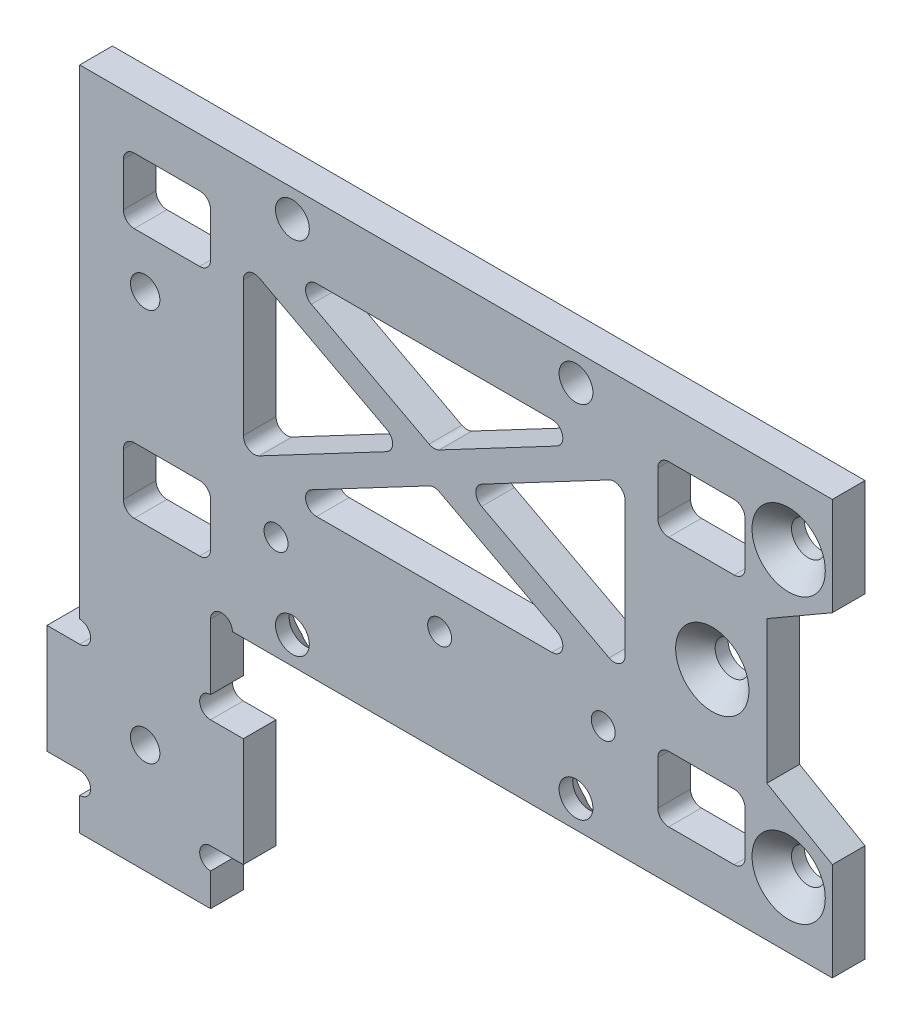
SolidWorks part; units mm, degrees
material "Thornel Mat VMA"
ref_plane "前视基准面" through (0, 0, 0) normal (0, 0, 1) x (1, 0, 0)
ref_plane "上视基准面" through (0, 0, 0) normal (0, 1, 0) x (1, 0, 0)
ref_plane "右视基准面" through (0, 0, 0) normal (1, 0, 0) x (0, 0, -1)
sketch "草图1" plane through (0, 0, 0) normal (0, 0, 1) x (1, 0, 0)
  line L0 (0, 0) -> (-12.4597, 0) construction
  line L1 (13, -16.5) -> (-13, -16.5) construction
  line L2 (13, -16.5) -> (13, 16.5) construction
  line L3 (13, 16.5) -> (-13, 16.5) construction
  line L4 (-13, -16.5) -> (-13, 16.5) construction
  line L5 (13, -16.5) -> (-13, 16.5) construction
  line L6 (13, 16.5) -> (-13, -16.5) construction
  line L7 (0, 0) -> (0, 10.3016) construction
  line L8 (-20.5, -14.5) -> (-28.5, -14.5)
  line L9 (36.5, -19) -> (-32.5, -19)
  line L10 (36.5, -19) -> (36.5, 19) construction
  line L12 (-36.5, -19) -> (-36.5, 19) construction
  line L13 (36.5, -19) -> (-36.5, 19) construction
  line L14 (36.5, 19) -> (-36.5, -19) construction
  line L15 (-20.5, 8.5) -> (-28.5, 8.5)
  line L16 (-20.5, 8.5) -> (-20.5, 14.5)
  line L17 (-20.5, 14.5) -> (-28.5, 14.5)
  line L18 (-28.5, 8.5) -> (-28.5, 14.5)
  line L19 (-20.5, 8.5) -> (-28.5, 14.5) construction
  line L20 (-20.5, 14.5) -> (-28.5, 8.5) construction
  line L21 (-28.5, -8.5) -> (-28.5, -14.5)
  line L22 (-20.5, -8.5) -> (-28.5, -8.5)
  line L23 (-20.5, -8.5) -> (-20.5, -14.5)
  line L24 (20.5, -8.5) -> (20.5, -14.5)
  line L25 (20.5, -8.5) -> (28.5, -8.5)
  line L26 (28.5, -8.5) -> (28.5, -14.5)
  line L27 (20.5, -14.5) -> (28.5, -14.5)
  line L28 (20.5, 14.5) -> (28.5, 14.5)
  line L29 (28.5, 8.5) -> (28.5, 14.5)
  line L30 (20.5, 8.5) -> (28.5, 8.5)
  line L31 (20.5, 8.5) -> (20.5, 14.5)
  line L32 (-28.5, -11.5) -> (-24.5, -11.5) construction
  line L33 (24.5, 14.5) -> (24.5, 12.5) construction
  line L34 (36.5, 19) -> (36.5, 10)
  line L35 (-32.5, 19) -> (-32.5, -19)
  line L44 (36.5, 19) -> (-32.5, 19)
  line L71 (32.5, 13) -> (32.5, -13) construction
  line L72 (25.5, 0) -> (32.5, 0) construction
  line L75 (36.5, 10) -> (30.5, 6.5359)
  line L76 (30.5, 6.5359) -> (30.5, -6.5359)
  line L77 (30.5, -6.5359) -> (36.5, -10)
  line L79 (36.5, -10) -> (36.5, -19)
  circle A0 centre (-13, 16.5) radius 1.55
  circle A1 centre (-13, -16.5) radius 1.55
  circle A2 centre (13, -16.5) radius 1.55
  circle A3 centre (13, 16.5) radius 1.55
  circle A4 centre (-32.5, 13) radius 1.55 construction
  circle A5 centre (-32.5, -13) radius 1.55 construction
  circle A6 centre (32.5, -13) radius 1.55
  circle A7 centre (32.5, 13) radius 1.55
  circle A18 centre (25.5, 0) radius 1.55
  point P0 (0, 0)
  point P25 (-24.5, 11.5)
  dimension "D1" = 3.1
  dimension "D2" = 33
  dimension "D3" = 26
  dimension "D4" = 26
  dimension "D5" = 65
  dimension "D6" = 2.5
  dimension "D7" = 4
  dimension "D8" = 6
  dimension "D9" = 8
  dimension "D10" = 49
  dimension "D11" = 23
  dimension "D15" = 4
  dimension "D23" = 7
  dimension "D24" = 9
  dimension "D25" = 5
  dimension "D26" = 60
extrude "凸台-拉伸1" add sketch "草图1" along normal blind 3
hole_wizard "M3 六角凹锥坑螺钉的锥形沉头孔1" positions "3D草图1" profile "草图2" countersink size "M3" standard "ISO" end condition through all
sketch3d "3D草图1"
  line L4 (32.5, 13, 3) -> (32.5, 13, 0) construction
  line L5 (25.5, 0, 3) -> (25.5, 0, 0) construction
  line L6 (32.5, -13, 3) -> (32.5, -13, 0) construction
  point P16 (32.5, 13, 3)
  point P20 (25.5, 0, 3)
  point P24 (32.5, -13, 3)
sketch "草图2" plane through (32.5, 13, 3) normal (1, 0, 0) x (0, -1, 0)
  line L0 (0, 0) -> (0, 3)
  line L1 (0, 3) -> (1.5, 3)
  line L2 (1.5, 3) -> (1.5, 1.86)
  line L3 (1.5, 1.86) -> (3.36, 0)
  line L5 (3.36, 0) -> (0, 0)
  line L6 (-1.5, 1.86) -> (-3.36, 0) construction
  line L11 (0, -6.35) -> (0, 107.95) construction
  dimension "通孔孔直径" = 3
  dimension "通孔孔深度" = 3
  dimension "近端锥形沉头孔直径" = 6.72
  dimension "近端锥形沉头孔角度" = 90
sketch "草图3" plane through (0, 0, 0) normal (0, 0, -1) x (-1, 0, 0)
  line L0 (14.5, -9.5) -> (-0.5, -9.5) construction
  line L1 (32.5, -19) -> (-36.5, -19) construction
  line L2 (26.5, 19) -> (26.5, 4) construction
  line L3 (-36.5, 19) -> (32.5, 19) construction
  line L4 (32.5, 19) -> (32.5, -19) construction
  line L5 (20.5, 8.5) -> (20.5, 14.5) construction
  line L6 (17.5, 12.5) -> (-17.5, 12.5) construction
  line L7 (17.5, 12.5) -> (17.5, -6) construction
  line L8 (17.5, -6) -> (-17.5, -6) construction
  line L9 (-17.5, 12.5) -> (-17.5, -6) construction
  line L10 (17.5, 12.5) -> (-17.5, -6) construction
  line L11 (17.5, -6) -> (-17.5, 12.5) construction
  line L12 (-20.5, 14.5) -> (-20.5, 8.5) construction
  line L13 (14.8251, -6) -> (0, 1.8361)
  line L14 (0, 1.8361) -> (-14.8251, -6)
  line L15 (-14.8251, -6) -> (14.8251, -6)
  line L16 (17.5, -4.5861) -> (2.6749, 3.25)
  line L17 (2.6749, 3.25) -> (17.5, 11.0861)
  line L18 (17.5, 11.0861) -> (17.5, -4.5861)
  line L19 (0, 12.5) -> (0, 3.25) construction
  line L20 (0, 3.25) -> (-17.5, 3.25) construction
  line L21 (0, 4.6639) -> (-14.8251, 12.5)
  line L22 (14.8251, 12.5) -> (0, 4.6639)
  line L23 (-14.8251, 12.5) -> (14.8251, 12.5)
  line L24 (-2.6749, 3.25) -> (-17.5, 11.0861)
  line L25 (-17.5, -4.5861) -> (-2.6749, 3.25)
  line L26 (-17.5, 11.0861) -> (-17.5, -4.5861)
  circle A0 centre (14.5, -9.5) radius 1.1
  circle A1 centre (-0.5, -9.5) radius 1.1
  circle A2 centre (-15.5, -9.5) radius 1.1
  circle A3 centre (26.5, 4) radius 1.35
  circle A4 centre (13, 16.5) radius 1.55 construction
  point P16 (0, 3.25)
  dimension "D3" = 2.2
  dimension "D6" = 15
  dimension "D8" = 2.7
  dimension "D2" = 9.5
  dimension "D4" = 15
  dimension "D5" = 0.5
  dimension "D7" = 6
  dimension "D9" = 3
  dimension "D10" = 3
  dimension "D11" = 4
  dimension "D12" = 3.5
  dimension "D13" = 2.5
  dimension "D1" = 3
extrude "切除-拉伸1" cut sketch "草图3" against normal through all
sketch "草图4" plane through (0, 0, 0) normal (0, 0, -1) x (-1, 0, 0)
  line L5 (32.5, -19) -> (20.5, -19)
  line L6 (32.5, -19) -> (32.5, -22)
  line L7 (32.5, -22) -> (20.5, -22) construction
  line L8 (20.5, -19) -> (20.5, -22)
  line L9 (26.5, -22) -> (26.5, -19) construction
  line L10 (32.5, -20.5) -> (20.5, -20.5) construction
  line L11 (32.5, -22) -> (20.5, -22) construction
  line L12 (32.5, -22) -> (32.5, -27)
  line L13 (32.5, -42) -> (20.5, -42)
  line L14 (20.5, -22) -> (20.5, -27)
  line L15 (26.5, -42) -> (26.5, -22) construction
  line L16 (35.5, -32) -> (17.5, -32) construction
  line L17 (35.5, -27) -> (32.5, -27)
  line L18 (35.5, -27) -> (35.5, -37)
  line L19 (35.5, -37) -> (32.5, -37)
  line L21 (35.5, -27) -> (32.5, -37) construction
  line L22 (35.5, -37) -> (32.5, -27) construction
  line L26 (20.5, -37) -> (20.5, -42)
  line L27 (32.5, -37) -> (32.5, -42)
  line L28 (32.5, -19) -> (-36.5, -19) construction
  line L29 (5.5, -22) -> (-5.5, -22) construction
  line L30 (5.5, -22) -> (5.5, -19) construction
  line L31 (5.5, -19) -> (-5.5, -19) construction
  line L32 (-5.5, -22) -> (-5.5, -19) construction
  line L33 (0, -19) -> (0, -22) construction
  line L34 (5.5, -20.5) -> (-5.5, -20.5) construction
  line L36 (17.5, -27) -> (20.5, -27)
  line L37 (17.5, -27) -> (17.5, -37)
  line L38 (17.5, -37) -> (20.5, -37)
  circle A0 centre (26.5, -32) radius 1.35
  circle A1 centre (26.5, 4) radius 1.35 construction
  point P7 (34, -32)
  point P116 (0, -20.5)
  point P124 (26.5, -20.5)
  point P139 (26.5, -32)
  dimension "D1" = 12
  dimension "D2" = 3
  dimension "D3" = 20
  dimension "D4" = 10
  dimension "D5" = 3
  dimension "D6" = 15
  dimension "D7" = 11
extrude "凸台-拉伸2" add sketch "草图4" against normal up to surface (3 mm away) up to face at (0, -3.388, 3)
sketch "草图5" plane through (0, 0, 0) normal (0, 0, -1) x (-1, 0, 0)
  line L1 (35.5, -32) -> (26.5, -32) construction
  line L2 (35.5, -37) -> (35.5, -27) construction
  line L3 (26.5, -32) -> (26.5, -42) construction
  line L4 (20.5, -42) -> (32.5, -42) construction
  line L5 (20.5, -19) -> (-36.5, -19) construction
  line L7 (32.5, -42) -> (32.5, -37) construction
  line L8 (32.5, -37) -> (35.5, -37) construction
  line L9 (20.5, -37) -> (20.5, -42) construction
  line L10 (20.5, -19) -> (20.5, -27) construction
  circle A1 centre (32.5, -38) radius 1
  circle A2 centre (32.5, -26) radius 1
  circle A4 centre (19.5, -19) radius 1
  circle A7 centre (20.5, -38) radius 1
  circle A8 centre (20.5, -26) radius 1
  dimension "D1" = 2
extrude "切除-拉伸2" cut sketch "草图5" against normal through all
fillet "圆角1" radius 1 28 edges at (-20.5, 8.5, 1.5) (-20.5, 14.5, 1.5) (-28.5, 14.5, 1.5) (-28.5, 8.5, 1.5) (-28.5, -8.5, 1.5) (-28.5, -14.5, 1.5) (-20.5, -14.5, 1.5) (-20.5, -8.5, 1.5) (20.5, -14.5, 1.5) (28.5, -14.5, 1.5) (28.5, -8.5, 1.5) (20.5, -8.5, 1.5) (28.5, 8.5, 1.5) (28.5, 14.5, 1.5) (20.5, 14.5, 1.5) (20.5, 8.5, 1.5) (0, 4.6639, 1.5) (14.8251, 12.5, 1.5) (17.5, -4.5861, 1.5) (17.5, 11.0861, 1.5) (2.6749, 3.25, 1.5) (-14.8251, 12.5, 1.5) (14.8251, -6, 1.5) (0, 1.8361, 1.5) (-14.8251, -6, 1.5) (-2.6749, 3.25, 1.5) (-17.5, 11.0861, 1.5) (-17.5, -4.5861, 1.5)
hole_wizard "打孔尺寸(%根据十字)槽沉头木螺钉的类型1" positions "3D草图2" profile "草图6" countersink size "M3" standard "GB" end condition through all
sketch3d "3D草图2"
  line L0 (-13, -16.5, 3) -> (-13, -16.5, 0) construction
  line L1 (13, -16.5, 3) -> (13, -16.5, 0) construction
  point P0 (-13, -16.5, 0)
  point P4 (13, -16.5, 0)
sketch "草图6" plane through (-13, -16.5, 0) normal (1, 0, 0) x (0, 1, 0)
  line L0 (0, 0) -> (0, 3)
  line L1 (0, 3) -> (1.55, 3)
  line L2 (1.55, 3) -> (1.55, 1.75)
  line L3 (1.55, 1.75) -> (3.3, 0)
  line L5 (3.3, 0) -> (0, 0)
  line L6 (-1.55, 1.75) -> (-3.3, 0) construction
  line L11 (0, -6.35) -> (0, 107.95) construction
  dimension "通孔孔直径" = 3.1
  dimension "通孔孔深度" = 3
  dimension "近端锥形沉头孔直径" = 6.6
  dimension "近端锥形沉头孔角度" = 90
